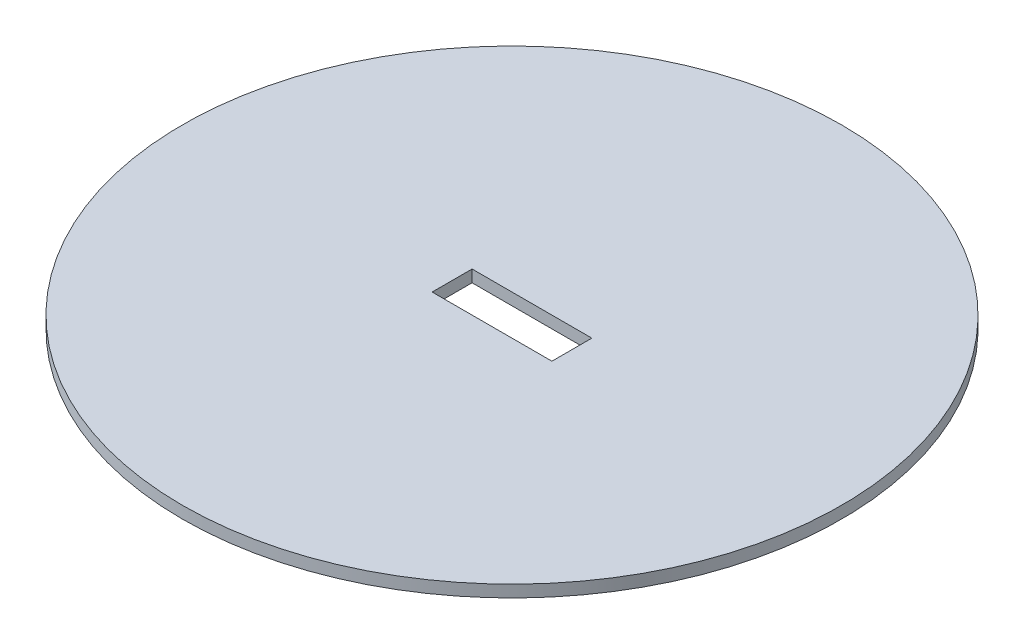
SolidWorks part; units mm, degrees
ref_plane "Front Plane" through (0, 0, 0) normal (0, 0, 1) x (1, 0, 0)
ref_plane "Top Plane" through (0, 0, 0) normal (0, 1, 0) x (1, 0, 0)
ref_plane "Right Plane" through (0, 0, 0) normal (1, 0, 0) x (0, 0, -1)
sketch "Sketch1" plane through (0, 0, 0) normal (0, 1, 0) x (1, 0, 0)
  circle A0 centre (0, 0) radius 82.55
  dimension "D1" = 165.1
extrude "Boss-Extrude1" add sketch "Sketch1" along normal blind 3
extrude "Cut-Extrude1" cut sketch "Sketch2" against normal blind 13
sketch "Sketch2" plane through (0, 3, 0) normal (0, 1, 0) x (1, 0, 0)
  line L1 (-15, 5) -> (15, 5)
  line L2 (-15, 5) -> (-15, -5)
  line L3 (-15, -5) -> (15, -5)
  line L4 (15, 5) -> (15, -5)
  line L5 (-15, 5) -> (15, -5) construction
  line L6 (-15, -5) -> (15, 5) construction
  point P0 (0, 0)
